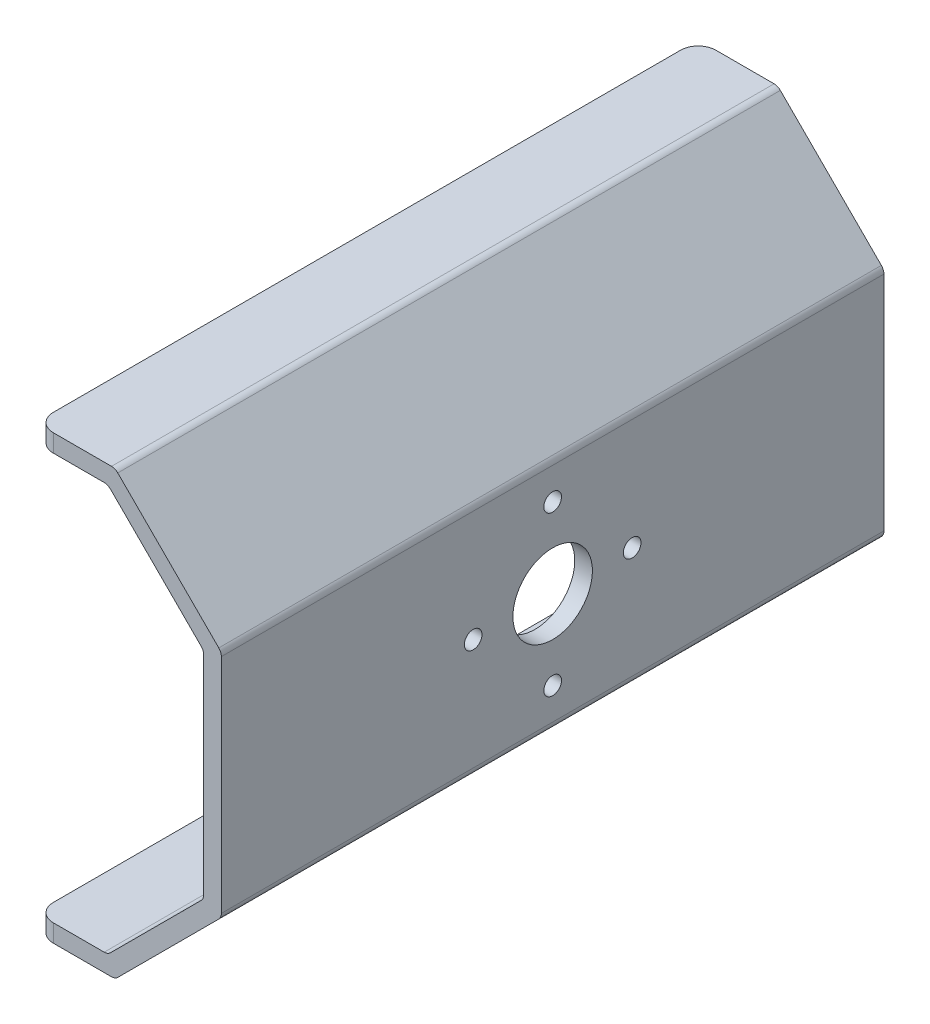
SolidWorks part; units mm, degrees
ref_plane "Plan de face" through (0, 0, 0) normal (0, 0, 1) x (1, 0, 0)
ref_plane "Plan de dessus" through (0, 0, 0) normal (0, 1, 0) x (1, 0, 0)
ref_plane "Plan de droite" through (0, 0, 0) normal (1, 0, 0) x (0, 0, -1)
sketch "Esquisse1" plane through (0, 0, 0) normal (0, 0, 1) x (1, 0, 0)
  line L0 (-7.6192, 27.1666) -> (1.3808, 27.1666)
  line L1 (1.3808, 27.1666) -> (13.4016, 15.1458)
  line L2 (13.4016, 15.1458) -> (13.4016, -10.8542)
  line L3 (13.4016, -10.8542) -> (1.3808, -22.875)
  line L4 (1.3808, -22.875) -> (-7.6192, -22.875)
  point P2 (0, 0)
  dimension "D1" = 135
  dimension "D2" = 9
  dimension "D3" = 26
  dimension "D4" = 17
  dimension "D5" = 17
  dimension "D6" = 135
  dimension "D7" = 9
  dimension "D8" = 50.0416
extrude "Extru.-Mince1" add sketch "Esquisse1" along normal blind 75 thin
sketch "Esquisse2" plane through (13.4016, 0, 0) normal (1, 0, 0) x (0, 0, -1)
  line L0 (-75, 2.1458) -> (0, 2.1458) construction
  line L1 (-75, 15.1458) -> (-75, -10.8542) construction
  line L2 (0, 15.1458) -> (0, -10.8542) construction
  line L3 (-37.5, 15.1458) -> (-37.5, -10.8542) construction
  line L4 (-75, 15.1458) -> (0, 15.1458) construction
  line L5 (-75, -10.8542) -> (0, -10.8542) construction
  circle A0 centre (-37.5, 2.1458) radius 4.5
  circle A1 centre (-46.5, 2.1458) radius 1
  circle A2 centre (-28.5, 2.1458) radius 1
  circle A3 centre (-37.5, 11.1458) radius 1
  circle A4 centre (-37.5, -6.8542) radius 1
  dimension "D1" = 9
  dimension "D2" = 2
  dimension "D4" = 2
  dimension "D3" = 9
  dimension "D5" = 9
extrude "Enlèv. mat.-Extru.1" cut sketch "Esquisse2" against normal blind 10
sketch "Esquisse3" plane through (0, 27.1666, 0) normal (0, 1, 0) x (1, 0, 0)
  line L0 (-7.6192, -37.5) -> (1.3808, -37.5) construction
  line L1 (-7.6192, -75) -> (-7.6192, 0) construction
  line L2 (1.3808, -75) -> (1.3808, 0) construction
  line L3 (-7.6192, 0) -> (1.3808, 0) construction
  circle A0 centre (-3.1192, -4.5) radius 2
  circle A1 centre (-3.1192, -70.5) radius 2
  dimension "D2" = 4
  dimension "D1" = 4.5
  dimension "D3" = 4.5
fillet "Congé1" radius 2 1 edges at (-7.6192, 26.1666, 0)
fillet "Congé2" radius 2 1 edges at (-7.6192, -21.875, 0)
fillet "Congé3" radius 2 1 edges at (-7.6192, -21.875, 75)
fillet "Congé4" radius 2 1 edges at (-7.6192, 26.1666, 75)
fillet "Congé5" radius 1 1 edges at (11.4016, 14.3174, 37.5)
fillet "Congé6" radius 1 1 edges at (11.4016, -10.0258, 37.5)
fillet "Congé7" radius 1 1 edges at (13.4016, -10.8542, 37.5)
fillet "Congé8" radius 1 1 edges at (13.4016, 15.1458, 37.5)
fillet "Congé9" radius 1 1 edges at (1.3808, 27.1666, 37.5)
fillet "Congé10" radius 1 1 edges at (1.3808, -22.875, 37.5)
fillet "Congé11" radius 1 1 edges at (0.5524, 25.1666, 37.5)
fillet "Congé12" radius 1 1 edges at (0.5524, -20.875, 37.5)
sketch "Esquisse4" plane through (0, 27.1666, 0) normal (0, 1, 0) x (1, 0, 0)
  line L1 (0.9666, -37.5) -> (-7.6192, -37.5) construction
  line L2 (0.9666, -75) -> (0.9666, 0) construction
  point P3 (-81.2456, -18.4466)
  point P10 (-83.8482, -0.1281)
